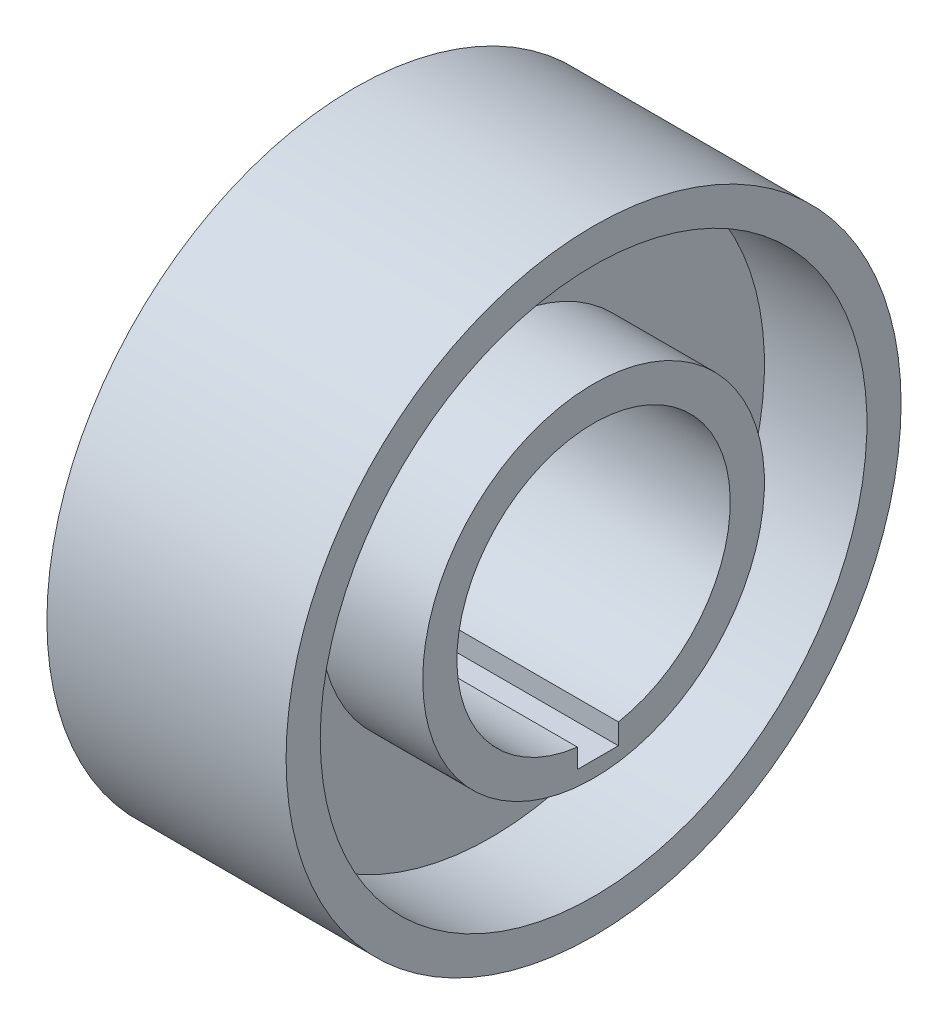
SolidWorks part; units mm, degrees
ref_plane "Front Plane" through (0, 0, 0) normal (0, 0, 1) x (1, 0, 0)
ref_plane "Top Plane" through (0, 0, 0) normal (0, 1, 0) x (1, 0, 0)
ref_plane "Right Plane" through (0, 0, 0) normal (1, 0, 0) x (0, 0, -1)
sketch "Sketch2" plane through (0, 0, 0) normal (0, 1, 0) x (1, 0, 0)
  line L0 (0, 0) -> (105.239, 0) construction
  line L1 (35, 20) -> (0, 20)
  line L2 (0, 20) -> (0, 25)
  line L3 (0, 25) -> (15, 25)
  line L4 (15, 25) -> (15, 40)
  line L5 (15, 40) -> (0, 40)
  line L6 (0, 40) -> (0, 45)
  line L7 (0, 45) -> (35, 45)
  line L8 (35, 45) -> (35, 40)
  line L9 (35, 40) -> (20, 40)
  line L10 (20, 40) -> (20, 25)
  line L11 (20, 25) -> (35, 25)
  line L12 (35, 25) -> (35, 20)
  dimension "D1" = 40
  dimension "D2" = 45
  dimension "D3" = 15
  dimension "D4" = 15
  dimension "D5" = 35
  dimension "D6" = 5
  dimension "D9" = 5
  dimension "D10" = 5
revolve "Revolve3" add sketch "Sketch2" angle 360 about L0
sketch "Sketch5" plane through (35, 0, 0) normal (1, 0, 0) x (0, 0, -1)
  line L0 (-2.3672, -22.6909) -> (3.6328, -22.6909)
  line L1 (3.6328, -22.6909) -> (3.6328, -19.8594)
  line L2 (-2.3672, -19.8594) -> (4.2127, -19.8594)
  line L3 (-2.3672, -22.6909) -> (-2.3672, -19.8594)
  circle A1 centre (0, 0) radius 20 construction
  point P3 (3.6328, -19.8594)
  circle M5 centre (0, 0) radius 20
  dimension "D1" = 6
extrude "Cut-Extrude1" cut sketch "Sketch5" against normal blind 35 contours L3 L0 L1 L2 M5
sketch "Sketch6" plane through (35, 0, 0) normal (1, 0, 0) x (0, 0, -1)
  line L0 (3.6328, -19.8594) -> (3.6328, -19.5928)
  line L1 (3.6328, -19.5928) -> (2.3672, -19.8594)
  line L2 (2.3672, -19.8594) -> (3.6328, -19.8594)
extrude "Cut-Extrude2" cut sketch "Sketch6" against normal blind 35
